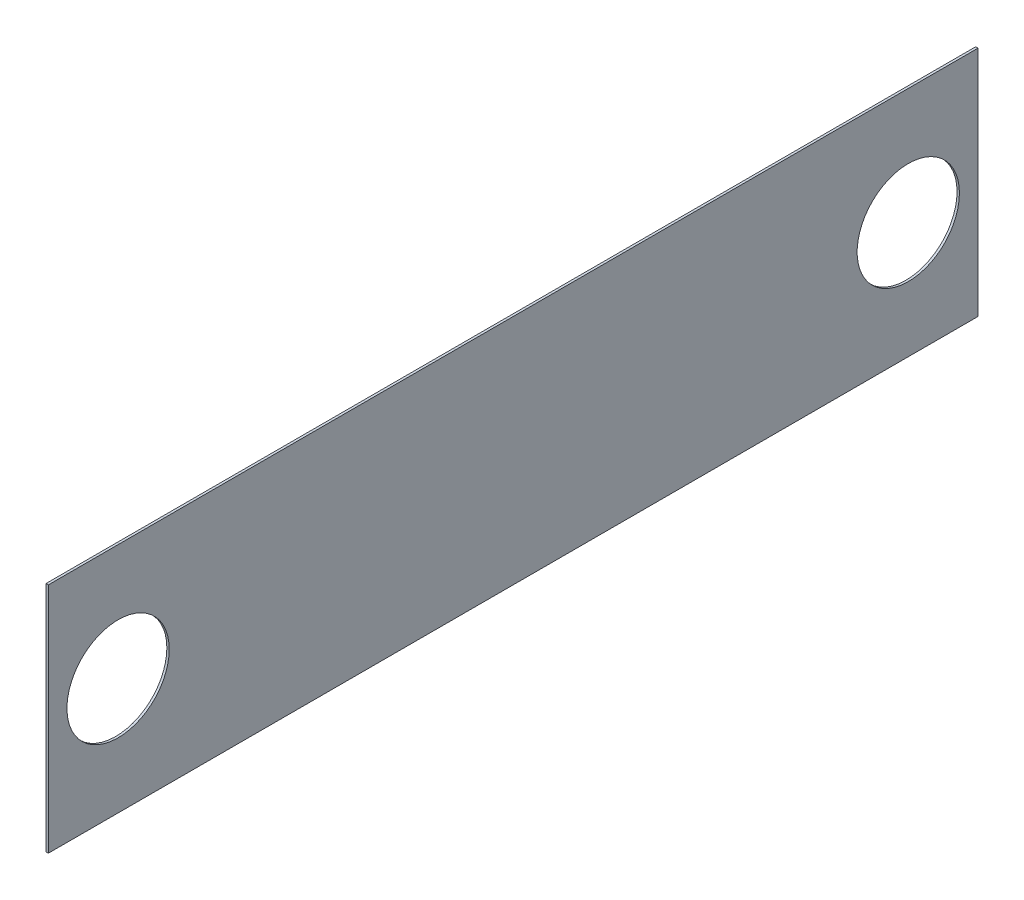
SolidWorks part; units mm, degrees
material "Low Carbon Steel"
ref_plane "Front Plane" through (0, 0, 0) normal (0, 0, 1) x (1, 0, 0)
ref_plane "Top Plane" through (0, 0, 0) normal (0, 1, 0) x (1, 0, 0)
ref_plane "Right Plane" through (0, 0, 0) normal (1, 0, 0) x (0, 0, -1)
sketch "Sketch1" plane through (0, 0, 0) normal (1, 0, 0) x (0, 0, -1)
  line L0 (-50, -12.5) -> (50, 12.5) construction
  line L1 (-50, 12.5) -> (50, 12.5)
  line L2 (-50, 12.5) -> (-50, -12.5)
  line L3 (-50, -12.5) -> (50, -12.5)
  line L4 (50, 12.5) -> (50, -12.5)
  dimension "D1" = 100
  dimension "D2" = 25
extrude "Boss-Extrude1" add sketch "Sketch1" along normal blind 0.254
hole_wizard "M10 Clearance Hole1" positions "Sketch2" profile "Sketch3" hole size "M10" standard "Peddi DIN" end condition through all
sketch "Sketch2" plane through (0.254, 0, 0) normal (1, 0, 0) x (0, 0, -1)
  line L0 (42.5, 0) -> (-42.5, 0) construction
  point P0 (-42.5, 0)
  point P2 (42.5, 0)
  dimension "D1" = 85
sketch "Sketch3" plane through (0.254, 0, 42.5) normal (0, 1, 0) x (0, 0, -1)
  line L0 (0, 0) -> (0, 0.254)
  line L1 (0, 0.254) -> (5.5, 0.254)
  line L2 (5.5, 0.254) -> (5.5, 0)
  line L5 (5.5, 0) -> (0, 0)
  line L11 (0, -6.35) -> (0, 107.95) construction
  dimension "Thru Hole Dia." = 11
  dimension "Thru Hole Depth" = 0.254
other "Freeze***"
